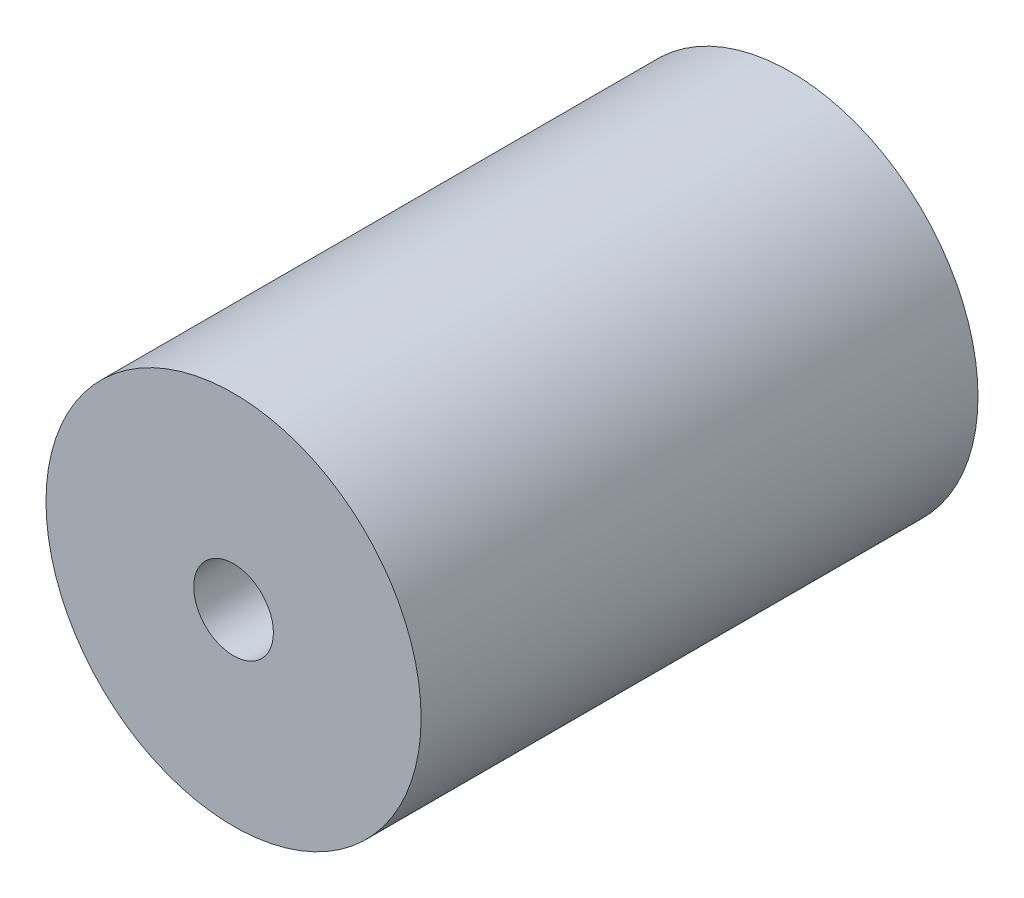
SolidWorks part; units mm, degrees
material "ABS"
ref_plane "Front Plane" through (0, 0, 0) normal (0, 0, 1) x (1, 0, 0)
ref_plane "Top Plane" through (0, 0, 0) normal (0, 1, 0) x (1, 0, 0)
ref_plane "Right Plane" through (0, 0, 0) normal (1, 0, 0) x (0, 0, -1)
sketch "Sketch1" plane through (0, 0, 0) normal (0, 0, 1) x (1, 0, 0)
  circle A0 centre (0, 0) radius 10
  circle A1 centre (0, 0) radius 2.125
  dimension "D1" = 20
  dimension "D2" = 4.25
extrude "Boss-Extrude1" add sketch "Sketch1" along normal blind 29.693
